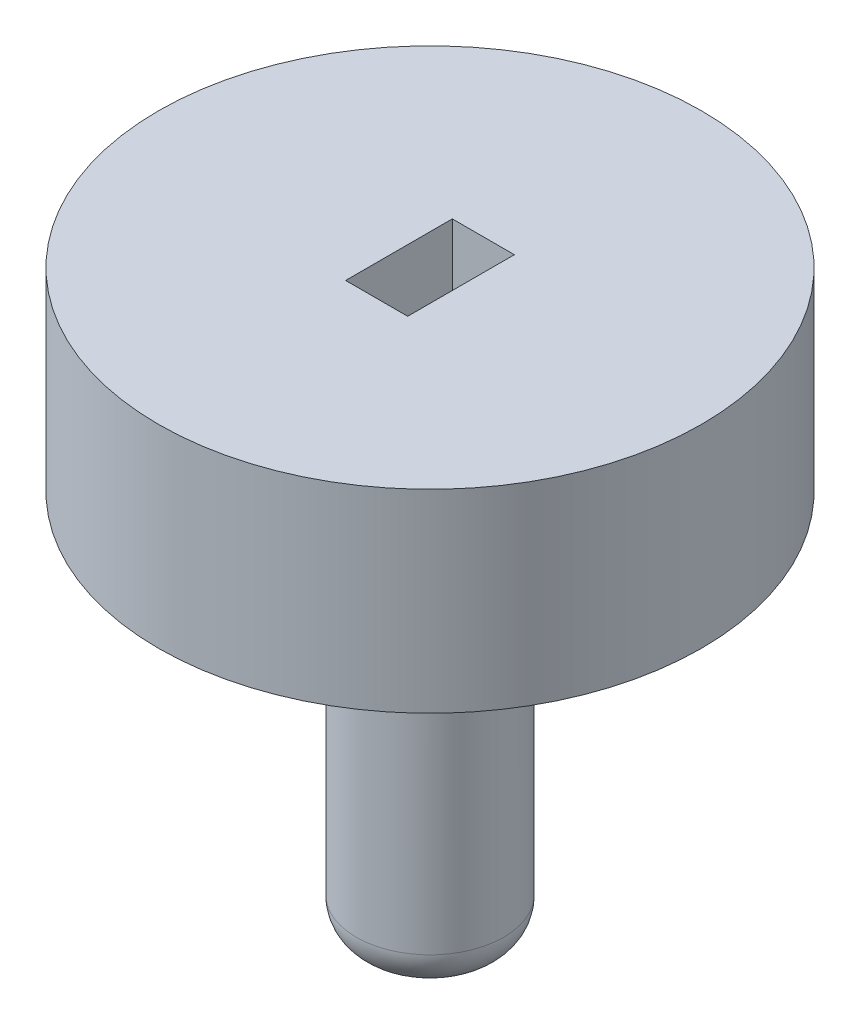
SolidWorks part; units mm, degrees
ref_plane "Спереди" through (0, 0, 0) normal (0, 0, 1) x (1, 0, 0)
ref_plane "Сверху" through (0, 0, 0) normal (0, 1, 0) x (1, 0, 0)
ref_plane "Справа" through (0, 0, 0) normal (1, 0, 0) x (0, 0, -1)
sketch "Эскиз1" plane through (0, 0, 0) normal (0, 1, 0) x (1, 0, 0)
  circle A0 centre (0, 0) radius 14
  arc A1 (-7.3832, 9.4598) -> (-8.5009, 8.4697) centre (0, 0) ccw
  arc A2 (-2.1414, 11.8074) -> (2.1414, 11.8074) centre (0, 12) ccw
  arc A3 (3.5911, 11.4501) -> (7.3832, 9.4598) centre (5.5767, 10.6255) ccw
  arc A4 (8.5009, 8.4697) -> (10.9337, 4.9451) centre (9.8758, 6.8168) ccw
  arc A5 (11.4632, 3.549) -> (11.9794, -0.7025) centre (11.9125, 1.4464) ccw
  arc A6 (11.7994, -2.1848) -> (10.2808, -6.1892) centre (11.2202, -4.2553) ccw
  arc A7 (9.4326, -7.418) -> (6.2269, -10.2579) centre (7.9575, -8.9821) ccw
  arc A8 (4.9048, -10.9518) -> (0.7466, -11.9768) centre (2.8718, -11.6513) ccw
  arc A9 (-0.7466, -11.9768) -> (-4.9048, -10.9518) centre (-2.8718, -11.6513) ccw
  arc A10 (-6.2269, -10.2579) -> (-9.4326, -7.418) centre (-7.9575, -8.9821) ccw
  arc A11 (-10.2808, -6.1892) -> (-11.7994, -2.1848) centre (-11.2202, -4.2553) ccw
  arc A12 (-11.9794, -0.7025) -> (-11.4632, 3.549) centre (-11.9125, 1.4464) ccw
  arc A13 (-10.9337, 4.9451) -> (-8.5009, 8.4697) centre (-9.8758, 6.8168) ccw
  arc A14 (-7.3832, 9.4598) -> (-3.5911, 11.4501) centre (-5.5767, 10.6255) ccw
  arc A15 (-2.1414, 11.8074) -> (-3.5911, 11.4501) centre (0, 0) ccw
  arc A16 (3.5911, 11.4501) -> (2.1414, 11.8074) centre (0, 0) ccw
  arc A17 (8.5009, 8.4697) -> (7.3832, 9.4598) centre (0, 0) ccw
  arc A18 (11.4632, 3.549) -> (10.9337, 4.9451) centre (0, 0) ccw
  arc A19 (11.7994, -2.1848) -> (11.9794, -0.7025) centre (0, 0) ccw
  arc A20 (9.4326, -7.418) -> (10.2808, -6.1892) centre (0, 0) ccw
  arc A21 (4.9048, -10.9518) -> (6.2269, -10.2579) centre (0, 0) ccw
  arc A22 (-0.7466, -11.9768) -> (0.7466, -11.9768) centre (0, 0) ccw
  arc A23 (-6.2269, -10.2579) -> (-4.9048, -10.9518) centre (0, 0) ccw
  arc A24 (-10.2808, -6.1892) -> (-9.4326, -7.418) centre (0, 0) ccw
  arc A25 (-11.9794, -0.7025) -> (-11.7994, -2.1848) centre (0, 0) ccw
  arc A26 (-10.9337, 4.9451) -> (-11.4632, 3.549) centre (0, 0) ccw
  point P45 (0, 0)
  dimension "D1" = 28
  dimension "D2" = 24
  dimension "D3" = 4.3
  dimension "D4" = 13
extrude "Бобышка-Вытянуть1" add sketch "Эскиз1" along normal blind 5 contours A0
sketch "Эскиз2" plane through (0, 5, 0) normal (0, 1, 0) x (1, 0, 0)
  circle A0 centre (0, 0) radius 14
  circle A1 centre (0, 0) radius 14 construction
extrude "Бобышка-Вытянуть2" add sketch "Эскиз2" along normal blind 5
sketch "Эскиз4" plane through (0, 5, 0) normal (0, -1, 0) x (1, 0, 0)
  circle A1 centre (0, 0) radius 3.8
  dimension "D1" = 7.6
extrude "Бобышка-Вытянуть3" add sketch "Эскиз4" along normal blind 25
fillet "Скругление1" radius 2 1 edges at (0, -20, -3.8)
sketch "Эскиз3" plane through (0, 10, 0) normal (0, 1, 0) x (1, 0, 0)
  line L1 (1.6, -2.75) -> (-1.6, -2.75)
  line L2 (1.6, -2.75) -> (1.6, 2.75)
  line L3 (1.6, 2.75) -> (-1.6, 2.75)
  line L4 (-1.6, -2.75) -> (-1.6, 2.75)
  line L5 (1.6, -2.75) -> (-1.6, 2.75) construction
  line L6 (1.6, 2.75) -> (-1.6, -2.75) construction
  point P0 (0, 0)
  dimension "D1" = 3.2
  dimension "D2" = 5.5
extrude "Вырез-Вытянуть1" cut sketch "Эскиз3" against normal blind 5.5
